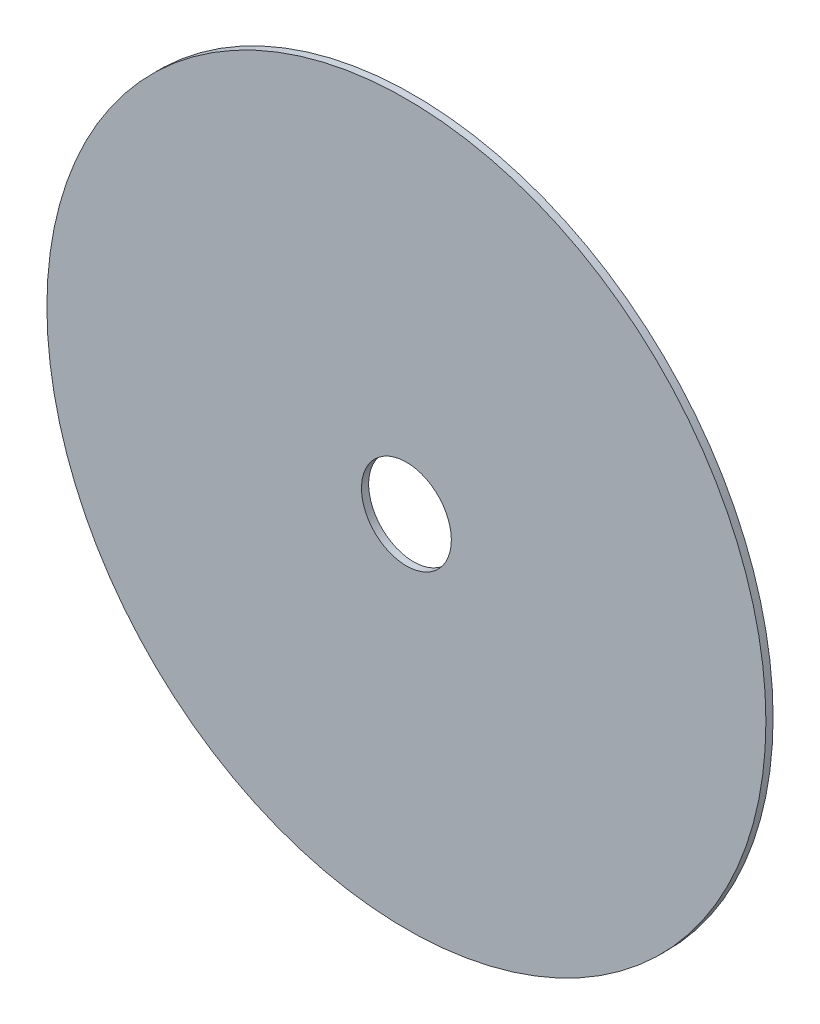
SolidWorks part; units mm, degrees
ref_plane "Plan de face" through (0, 0, 0) normal (0, 0, 1) x (1, 0, 0)
ref_plane "Plan de dessus" through (0, 0, 0) normal (0, 1, 0) x (1, 0, 0)
ref_plane "Plan de droite" through (0, 0, 0) normal (1, 0, 0) x (0, 0, -1)
sketch "Esquisse1" plane through (0, 0, 0) normal (0, 0, 1) x (1, 0, 0)
  circle A0 centre (0, 0) radius 7.5
  circle A1 centre (0, 0) radius 60
  circle A2 centre (0, 0) radius 23
  circle A3 centre (0, 0) radius 25
  circle A4 centre (0, 0) radius 58
  dimension "D1" = 15
  dimension "D2" = 120
  dimension "D3" = 46
  dimension "D4" = 50
  dimension "D5" = 116
extrude "Boss.-Extru.1" add sketch "Esquisse1" along normal blind 1.2 contours A1 A4 | A2 A0 | A3 A2 | A4 A3
